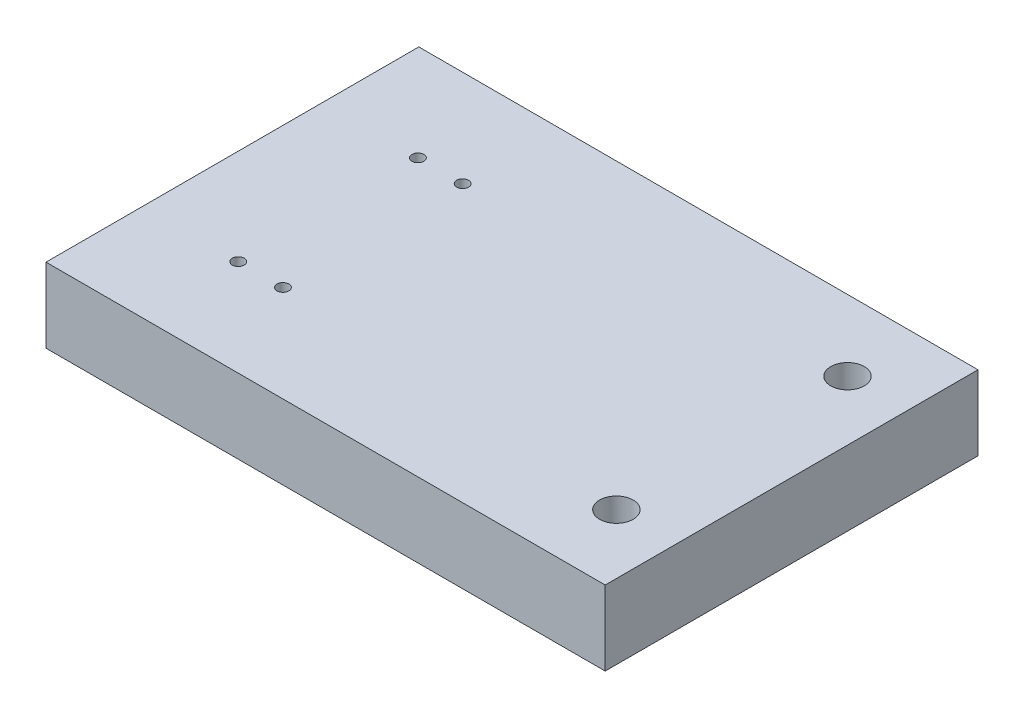
SolidWorks part; units mm, degrees
ref_plane "Front Plane" through (0, 0, 0) normal (0, 0, 1) x (1, 0, 0)
ref_plane "Top Plane" through (0, 0, 0) normal (0, 1, 0) x (1, 0, 0)
ref_plane "Right Plane" through (0, 0, 0) normal (1, 0, 0) x (0, 0, -1)
sketch "Sketch2" plane through (0, 0, 0) normal (0, 1, 0) x (1, 0, 0)
  line L1 (-37.5, 25) -> (37.5, 25)
  line L2 (-37.5, 25) -> (-37.5, -25)
  line L3 (-37.5, -25) -> (37.5, -25)
  line L4 (37.5, 25) -> (37.5, -25)
  line L5 (-37.5, 25) -> (37.5, -25) construction
  line L6 (-37.5, -25) -> (37.5, 25) construction
  point P0 (0, 0)
  dimension "D1" = 50
  dimension "D2" = 75
extrude "Plate_topview" add sketch "Sketch2" along normal blind 10
ref_plane "Midplane_topview" through (0, 5, 0) normal (0, 1, 0) x (1, 0, 0)
sketch "channel_sketch" plane through (0, 5, 0) normal (0, 1, 0) x (1, 0, 0)
  line L1 (3.9279, 0.5) -> (2.478, 2.3123)
  line L2 (37.5, -25) -> (37.5, 25) construction
  line L4 (25, 7.5) -> (28.85, 7.5)
  line L5 (24.5, 7) -> (24.5, 0.5)
  line L6 (25, -7.5) -> (28.85, -7.5)
  line L7 (34.5, 7) -> (34.5, -7)
  line L25 (-2.4318, 2.5) -> (2.0876, 2.5)
  line L27 (-2.4318, -2.5) -> (2.0876, -2.5)
  line L32 (3.9279, -0.5) -> (2.478, -2.3123)
  line L33 (-4.2721, 0.5) -> (-2.8222, 2.3123)
  line L34 (-4.2721, -0.5) -> (-2.8222, -2.3123)
  line L44 (5.0779, -0.5) -> (3.9279, -0.5)
  line L45 (5.3279, -14.5) -> (5.3279, -0.75)
  line L46 (8.3279, -15.5) -> (6.3279, -15.5)
  line L47 (9.3279, 14.2341) -> (9.3279, -14.5)
  line L48 (11.0779, 14.4841) -> (9.5779, 14.4841)
  line L49 (11.3279, -14.5) -> (11.3279, 14.2341)
  line L50 (14.3279, -15.5) -> (12.3279, -15.5)
  line L51 (15.3279, 14.2341) -> (15.3279, -14.5)
  line L52 (17.0779, 14.4841) -> (15.5779, 14.4841)
  line L53 (17.3279, -14.5) -> (17.3279, 14.2341)
  line L54 (20.3279, -15.5) -> (18.3279, -15.5)
  line L55 (21.3279, -0.75) -> (21.3279, -14.5)
  line L56 (21.5779, -0.5) -> (24.5, -0.5)
  line L57 (-4.2721, 0.5) -> (-7.965, 0.5)
  line L58 (-8.8792, 0) -> (-12.4305, -3.5513)
  line L59 (-12.4305, -3.5513) -> (-18.1721, -3.5513)
  line L60 (-19.1721, -4.5513) -> (-19.1721, -11.4923)
  line L61 (-7.965, 0.5) -> (-11.9431, 4.4781)
  line L62 (-12.1198, 4.5513) -> (-18.1721, 4.5513)
  line L63 (-18.1721, 4.5513) -> (-18.1721, 11.4923)
  line L64 (-23.9221, 4.5513) -> (-19.1721, 4.5513)
  line L65 (-24.1721, 4.8013) -> (-24.1721, 11.4923)
  line L66 (-18.1721, -3.5513) -> (-24.1721, -3.5513)
  line L67 (-25.1721, -4.5513) -> (-25.1721, -11.4923)
  line L68 (5.3279, 0.5) -> (3.9279, 0.5)
  line L69 (6.3279, -14.25) -> (6.3279, -0.5)
  line L70 (8.0779, -14.5) -> (6.5779, -14.5)
  line L71 (8.3279, 14.4841) -> (8.3279, -14.25)
  line L72 (11.3279, 15.4841) -> (9.3279, 15.4841)
  line L73 (12.3279, -14.25) -> (12.3279, 14.4841)
  line L74 (14.0779, -14.5) -> (12.5779, -14.5)
  line L75 (14.3279, 14.4841) -> (14.3279, -14.25)
  line L76 (17.3279, 15.4841) -> (15.3279, 15.4841)
  line L77 (18.3279, -14.25) -> (18.3279, 14.4841)
  line L78 (20.0779, -14.5) -> (18.5779, -14.5)
  line L79 (20.3279, -0.5) -> (20.3279, -14.25)
  line L80 (21.3279, 0.5) -> (24.5, 0.5)
  line L81 (-4.2721, -0.5) -> (-7.965, -0.5)
  line L82 (-7.965, -0.5) -> (-11.9431, -4.4781)
  line L83 (-12.1198, -4.5513) -> (-18.1721, -4.5513)
  line L84 (-18.1721, -4.5513) -> (-18.1721, -11.4923)
  line L85 (-8.8792, 0) -> (-12.4305, 3.5513)
  line L86 (-12.4305, 3.5513) -> (-18.1721, 3.5513)
  line L87 (-19.1721, 4.5513) -> (-19.1721, 11.4923)
  line L88 (-18.1721, 3.5513) -> (-24.1721, 3.5513)
  line L89 (-25.1721, 4.5513) -> (-25.1721, 11.4923)
  line L90 (-19.1721, -4.5513) -> (-23.9221, -4.5513)
  line L91 (-24.1721, -4.8013) -> (-24.1721, -11.4923)
  line L100 (24.5, -0.5) -> (24.5, -7)
  line L129 (30.15, 7.5) -> (34, 7.5)
  line L130 (30.15, -7.5) -> (34, -7.5)
  line L131 (30.15, 7.5) -> (30.15, 13.5558)
  line L132 (28.85, -7.5) -> (28.85, -13.5558)
  line L133 (28.85, 7.5) -> (28.85, 13.5558)
  line L134 (30.15, -7.5) -> (30.15, -13.5558)
  arc A2 (11.3279, 14.2341) -> (11.0779, 14.4841) centre (11.0779, 14.2341) ccw
  arc A3 (9.3279, 14.2341) -> (9.5779, 14.4841) centre (9.5779, 14.2341) cw
  arc A8 (-2.4318, 2.5) -> (-2.8222, 2.3123) centre (-2.4318, 2) ccw
  arc A9 (2.0876, 2.5) -> (2.478, 2.3123) centre (2.0876, 2) cw
  arc A10 (2.0876, -2.5) -> (2.478, -2.3123) centre (2.0876, -2) ccw
  arc A11 (-2.8222, -2.3123) -> (-2.4318, -2.5) centre (-2.4318, -2) ccw
  arc A20 (34, -7.5) -> (34.5, -7) centre (34, -7) ccw
  arc A21 (24.5, -7) -> (25, -7.5) centre (25, -7) ccw
  arc A22 (25, 7.5) -> (24.5, 7) centre (25, 7) ccw
  arc A23 (34, 7.5) -> (34.5, 7) centre (34, 7) cw
  arc A24 (-23.9221, 4.5513) -> (-24.1721, 4.8013) centre (-23.9221, 4.8013) cw
  arc A25 (6.3279, -15.5) -> (5.3279, -14.5) centre (6.3279, -14.5) cw
  arc A26 (9.3279, -14.5) -> (8.3279, -15.5) centre (8.3279, -14.5) cw
  arc A29 (12.3279, -15.5) -> (11.3279, -14.5) centre (12.3279, -14.5) cw
  arc A30 (15.3279, -14.5) -> (14.3279, -15.5) centre (14.3279, -14.5) cw
  arc A31 (17.3279, 14.2341) -> (17.0779, 14.4841) centre (17.0779, 14.2341) ccw
  arc A32 (6.5779, -14.5) -> (6.3279, -14.25) centre (6.5779, -14.25) cw
  arc A33 (18.3279, -15.5) -> (17.3279, -14.5) centre (18.3279, -14.5) cw
  arc A34 (21.3279, -14.5) -> (20.3279, -15.5) centre (20.3279, -14.5) cw
  arc A35 (-11.9431, 4.4781) -> (-12.1198, 4.5513) centre (-12.1198, 4.3013) ccw
  arc A39 (-24.1721, -3.5513) -> (-25.1721, -4.5513) centre (-24.1721, -4.5513) ccw
  arc A40 (6.3279, -0.5) -> (5.3279, 0.5) centre (5.3279, -0.5) ccw
  arc A41 (8.0779, -14.5) -> (8.3279, -14.25) centre (8.0779, -14.25) ccw
  arc A42 (12.5779, -14.5) -> (12.3279, -14.25) centre (12.5779, -14.25) cw
  arc A43 (9.3279, 15.4841) -> (8.3279, 14.4841) centre (9.3279, 14.4841) ccw
  arc A44 (12.3279, 14.4841) -> (11.3279, 15.4841) centre (11.3279, 14.4841) ccw
  arc A45 (14.0779, -14.5) -> (14.3279, -14.25) centre (14.0779, -14.25) ccw
  arc A46 (20.0779, -14.5) -> (20.3279, -14.25) centre (20.0779, -14.25) ccw
  arc A47 (15.3279, 15.4841) -> (14.3279, 14.4841) centre (15.3279, 14.4841) ccw
  arc A48 (18.3279, 14.4841) -> (17.3279, 15.4841) centre (17.3279, 14.4841) ccw
  arc A49 (21.3279, -0.75) -> (21.5779, -0.5) centre (21.5779, -0.75) cw
  arc A50 (18.5779, -14.5) -> (18.3279, -14.25) centre (18.5779, -14.25) cw
  arc A51 (21.3279, 0.5) -> (20.3279, -0.5) centre (21.3279, -0.5) ccw
  arc A53 (15.5779, 14.4841) -> (15.3279, 14.2341) centre (15.5779, 14.2341) ccw
  arc A54 (-24.1721, 3.5513) -> (-25.1721, 4.5513) centre (-24.1721, 4.5513) cw
  arc A55 (-24.1721, 11.4923) -> (-25.1721, 11.4923) centre (-24.6721, 12.0513) ccw
  arc A66 (-11.9431, -4.4781) -> (-12.1198, -4.5513) centre (-12.1198, -4.3013) cw
  arc A67 (5.3279, -0.75) -> (5.0779, -0.5) centre (5.0779, -0.75) ccw
  arc A69 (-24.1721, -4.8013) -> (-23.9221, -4.5513) centre (-23.9221, -4.8013) cw
  arc A71 (-18.1721, 11.4923) -> (-19.1721, 11.4923) centre (-18.6721, 12.0513) ccw
  arc A72 (-19.1721, -11.4923) -> (-18.1721, -11.4923) centre (-18.6721, -12.0513) ccw
  arc A73 (-25.1721, -11.4923) -> (-24.1721, -11.4923) centre (-24.6721, -12.0513) ccw
  arc A74 (30.15, 13.5558) -> (28.85, 13.5558) centre (29.5, 15.5) ccw
  arc A75 (28.85, -13.5558) -> (30.15, -13.5558) centre (29.5, -15.5) ccw
  point P6 (29.5, 0)
  point P14 (20.8279, 0)
  point P42 (-24.6721, -4.0513)
  point P48 (-24.6721, 4.0513)
  point P54 (8.8279, 14.9841)
  point P57 (11.8279, 14.9841)
  point P60 (14.8279, 14.9841)
  point P63 (17.8279, 14.9841)
  point P80 (5.8279, -15)
  point P83 (8.8279, -15)
  point P86 (11.8279, -15)
  point P89 (14.8279, -15)
  point P92 (17.8279, -15)
  point P95 (20.8279, -15)
  point P98 (20.8279, 0)
  dimension "D18" = 0.25
  dimension "D19" = 0.25
  dimension "D20" = 0.25
  dimension "D21" = 0.25
  dimension "D22" = 0.25
  dimension "D23" = 0.25
  dimension "D24" = 0.25
  dimension "D25" = 1.5
  dimension "D26" = 1.5
  dimension "D27" = 1.5
  dimension "D28" = 1.5
  dimension "D33" = 4.1
  dimension "D34" = 4.1
  dimension "D9" = 0.25
  dimension "D1" = 3
  dimension "D4" = 3
  dimension "D5" = 3
  dimension "D6" = 3
  dimension "D7" = 3
  dimension "D8" = 3
extrude "Channel" cut sketch "channel_sketch" against normal mid plane 2
sketch "connetion_sketch" plane through (0, 5, 0) normal (0, 1, 0) x (1, 0, 0)
  circle A0 centre (-24.6721, 12.0513) radius 0.8
  circle A1 centre (-18.6721, 12.0513) radius 0.8
  circle A2 centre (-18.6721, -12.0513) radius 0.8
  circle A3 centre (-24.6721, -12.0513) radius 0.8
  circle A4 centre (29.5, 15.5) radius 2.25
  circle A5 centre (29.5, -15.5) radius 2.25
  dimension "D1" = 1.6
  dimension "D2" = 1.6
  dimension "D3" = 1.6
  dimension "D4" = 1.6
  dimension "D5" = 4.5
  dimension "D6" = 4.5
extrude "Connecting_port" cut sketch "connetion_sketch" along normal blind 12
